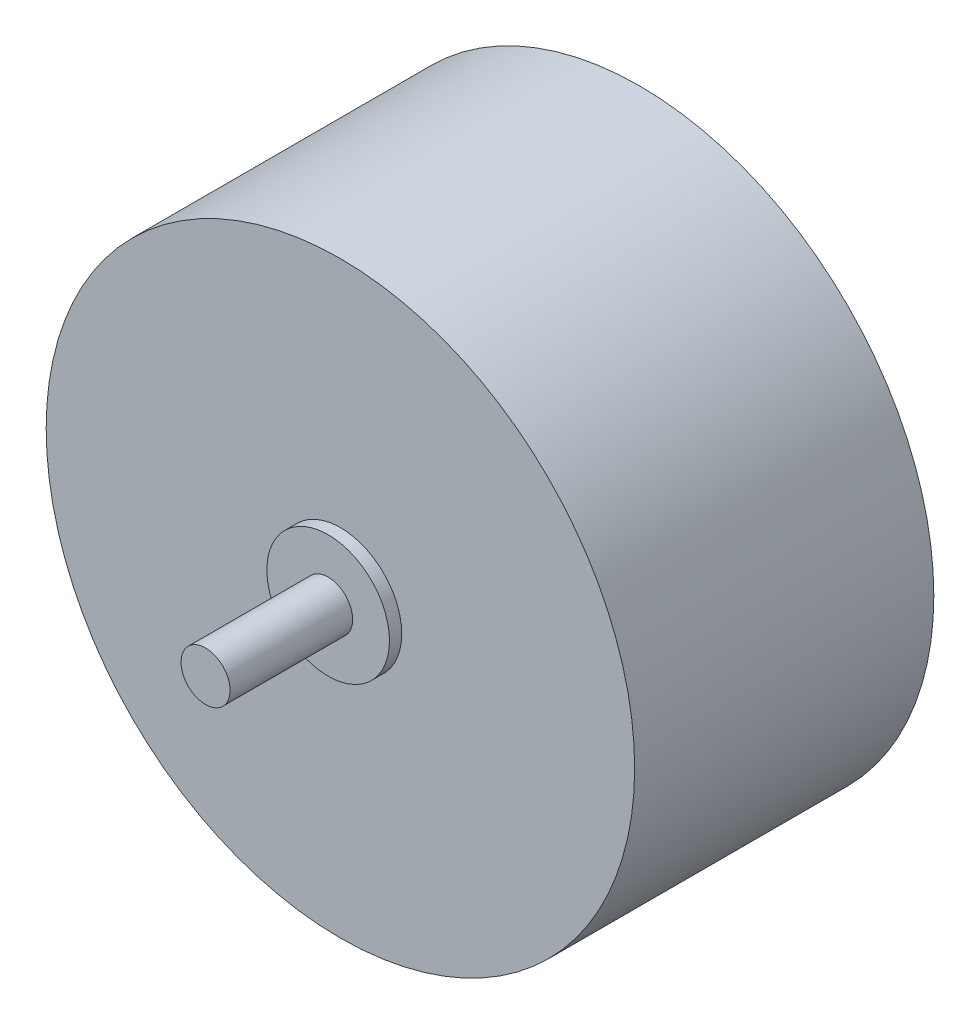
SolidWorks part; units mm, degrees
material "Aluminum Bronze"
ref_plane "Front Plane" through (0, 0, 0) normal (0, 0, 1) x (1, 0, 0)
ref_plane "Top Plane" through (0, 0, 0) normal (0, 1, 0) x (1, 0, 0)
ref_plane "Right Plane" through (0, 0, 0) normal (1, 0, 0) x (0, 0, -1)
sketch "Sketch1" plane through (0, 0, 0) normal (0, 0, 1) x (1, 0, 0)
  circle A0 centre (0, 0) radius 12
  dimension "D1" = 24
extrude "Boss-Extrude1" add sketch "Sketch1" along normal blind 12.2 contours A0
sketch "Sketch2" plane through (0, 0, 12.2) normal (0, 0, 1) x (1, 0, 0)
  circle A0 centre (0, 0) radius 2.5
  dimension "D1" = 5
extrude "Boss-Extrude2" add sketch "Sketch2" along normal blind 0.5
sketch "Sketch3" plane through (0, 0, 12.7) normal (0, 0, 1) x (1, 0, 0)
  circle A0 centre (0, 0) radius 1
  dimension "D1" = 2
extrude "Boss-Extrude3" add sketch "Sketch3" along normal blind 5
